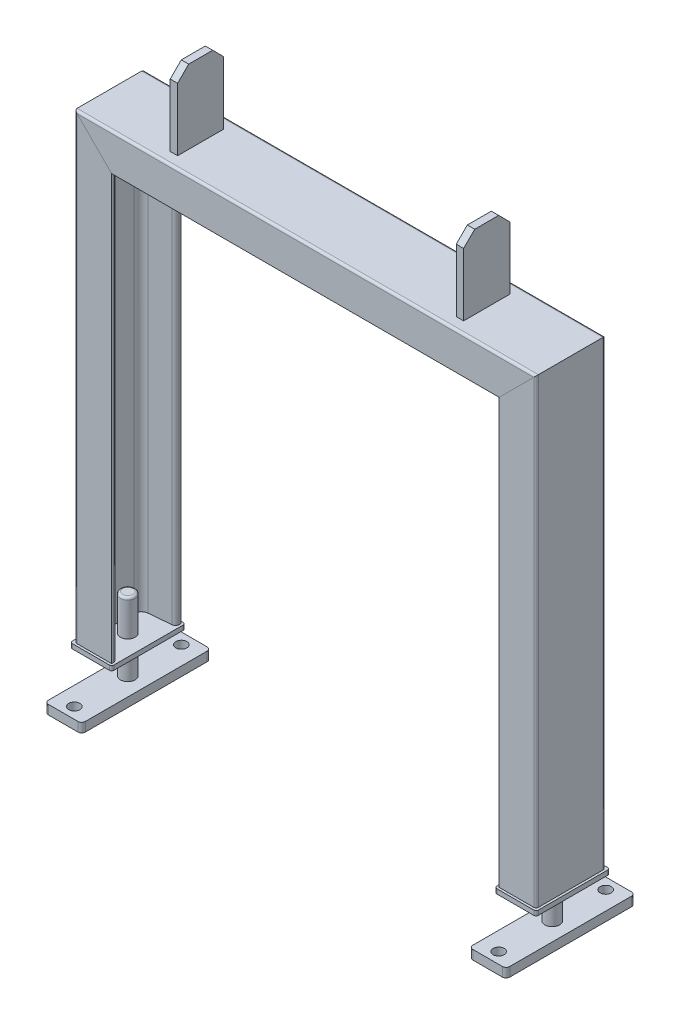
SolidWorks part; units mm, degrees
material "AISI 1015 Steel, Cold Drawn (SS)"
ref_plane "Front Plane" through (0, 0, 0) normal (0, 0, 1) x (1, 0, 0)
ref_plane "Top Plane" through (0, 0, 0) normal (0, 1, 0) x (1, 0, 0)
ref_plane "Right Plane" through (0, 0, 0) normal (1, 0, 0) x (0, 0, -1)
sketch "Sketch1" plane through (0, 0, 0) normal (0, 0, 1) x (1, 0, 0)
  line L0 (250, 0) -> (-250, 0)
  line L1 (-250, 0) -> (-250, -500)
  line L2 (250, 0) -> (250, -500)
  point P4 (0, 0)
  dimension "D1" = 500
  dimension "D2" = 500
other "Channel C 75 X 40 X 5.0(1)"
ref_plane "Plane1" through (-250, 0, -37.5) normal (0, -1, 0) x (1, 0, 0)
sketch "Sketch14" plane through (-250, 0, -37.5) normal (0, -1, 0) x (1, 0, 0)
  line L0 (40, 75) -> (0, 75)
  line L1 (40, 0) -> (0, 0)
  line L2 (0, 75) -> (0, 0)
  line L5 (0, 7) -> (22.5, 7) construction
  line L6 (40, 75) -> (40, 73.1964)
  line L7 (40, 0) -> (40, 1.8036)
  line L8 (5, 37.5) -> (0, 37.5) construction
  line L12 (5, 59.1383) -> (5, 15.8617)
  line L17 (12.3028, 67.1079) -> (36.3486, 69.2116)
  line L18 (12.3028, 7.8921) -> (36.3486, 5.7884)
  arc A0 (36.3486, 69.2116) -> (40, 73.1964) centre (36, 73.1964) ccw
  arc A1 (36.3486, 5.7884) -> (40, 1.8036) centre (36, 1.8036) cw
  arc A9 (5, 15.8617) -> (12.3028, 7.8921) centre (13, 15.8617) ccw
  arc A10 (5, 59.1383) -> (12.3028, 67.1079) centre (13, 59.1383) cw
  point P10 (20, 75)
  point P11 (20, 0)
  point P14 (0, 0)
  dimension "D4" = 17.5
  dimension "RI" = 8
  dimension "D2" = 5
  dimension "RA" = 4
  dimension "Depth" = 75
  dimension "BF" = 40
  dimension "TW" = 5
  dimension "TF" = 7
sketch "Sketch15" plane through (0, -500, 0) normal (0, -1, 0) x (1, 0, 0)
  line L0 (-252.5, 37.5) -> (-252.5, -37.5)
  line L1 (-250, 37.5) -> (-210, 37.5) construction
  line L3 (-250, -37.5) -> (-210, -37.5) construction
  line L5 (250, -37.5) -> (210, -37.5) construction
  line L6 (250, -37.5) -> (250, 37.5) construction
  line L7 (250, 37.5) -> (210, 37.5) construction
  line L8 (210, -37.5) -> (210, 37.5) construction
  line L9 (-250, -40) -> (-210, -40)
  line L10 (-207.5, 37.5) -> (-207.5, -37.5)
  line L11 (-250, 40) -> (-210, 40)
  line L12 (252.5, -37.5) -> (252.5, 37.5)
  line L13 (250, 40) -> (210, 40)
  line L14 (207.5, -37.5) -> (207.5, 37.5)
  line L15 (250, -40) -> (210, -40)
  line L16 (252.5, 40) -> (207.5, 40) construction
  line L17 (252.5, -40) -> (252.5, 40) construction
  line L18 (207.5, -40) -> (207.5, 40) construction
  line L19 (252.5, -40) -> (207.5, -40) construction
  line L20 (-252.5, 40) -> (-252.5, -40) construction
  line L21 (-252.5, -40) -> (-207.5, -40) construction
  line L22 (-207.5, 40) -> (-207.5, -40) construction
  line L23 (-252.5, 40) -> (-207.5, 40) construction
  line L24 (-250, 37.5) -> (-250, -37.5) construction
  line L25 (-210, 37.5) -> (-210, -37.5) construction
  line L26 (0, -55) -> (0, 55) construction
  line L27 (-210, 37.5) -> (-250, 37.5) construction
  line L28 (-210, 37.5) -> (-210, -37.5) construction
  line L29 (-210, -37.5) -> (-250, -37.5) construction
  line L30 (-250, 37.5) -> (-250, -37.5) construction
  line L31 (-210, 37.5) -> (-250, -37.5) construction
  line L32 (-210, -37.5) -> (-250, 37.5) construction
  arc A0 (250, 40) -> (252.5, 37.5) centre (250, 37.5) cw
  arc A1 (210, 40) -> (207.5, 37.5) centre (210, 37.5) ccw
  arc A2 (207.5, -37.5) -> (210, -40) centre (210, -37.5) ccw
  arc A3 (252.5, -37.5) -> (250, -40) centre (250, -37.5) cw
  arc A4 (-252.5, -37.5) -> (-250, -40) centre (-250, -37.5) ccw
  arc A5 (-210, -40) -> (-207.5, -37.5) centre (-210, -37.5) ccw
  arc A6 (-207.5, 37.5) -> (-210, 40) centre (-210, 37.5) ccw
  arc A7 (-250, 40) -> (-252.5, 37.5) centre (-250, 37.5) ccw
  circle A8 centre (-230, 0) radius 8
  circle A9 centre (230, 0) radius 8
  point P44 (-230, 0)
  dimension "D3" = 2.5
  dimension "D4" = 2.5
  dimension "D5" = 2.5
  dimension "D6" = 2.5
  dimension "D7" = 2.5
  dimension "D8" = 2.5
  dimension "D9" = 2.5
  dimension "D10" = 2.5
  dimension "D11" = 16
  dimension "D1" = 2.5
  dimension "D2" = 2.5
extrude "Boss-Extrude1" add sketch "Sketch15" along normal blind 5 separate body
fillet "Fillet1" radius 2.5 2 edges at (-250, -250, -37.5) (-250, -250, 37.5)
fillet "Fillet2" radius 2.5 2 edges at (0, 0, -37.5) (0, 0, 37.5)
fillet "Fillet3" radius 2.5 2 edges at (250, -250, -37.5) (250, -250, 37.5)
sketch "Sketch16" plane through (0, 0, 0) normal (0, 1, 0) x (1, 0, 0)
  line L0 (155, 0) -> (-155, 0)
  line L1 (0, -55) -> (0, 55) construction
  line L2 (-159, -25) -> (-151, -25)
  line L3 (-159, -25) -> (-159, 25)
  line L4 (-159, 25) -> (-151, 25)
  line L5 (-151, -25) -> (-151, 25)
  line L6 (-159, -25) -> (-151, 25) construction
  line L7 (-159, 25) -> (-151, -25) construction
  line L8 (159, 25) -> (151, -25) construction
  line L9 (159, -25) -> (151, 25) construction
  line L10 (151, -25) -> (151, 25)
  line L11 (159, 25) -> (151, 25)
  line L12 (159, -25) -> (159, 25)
  line L13 (159, -25) -> (151, -25)
  point P14 (0, 0)
  dimension "D1" = 8
  dimension "D2" = 50
  dimension "D3" = 151
extrude "Boss-Extrude2" add sketch "Sketch16" along normal blind 80 separate body
chamfer "Chamfer1" distance 12 2 edges at (-155, 80, -25) (-155, 80, 25)
chamfer "Chamfer2" distance 12 angle 45 2 edges at (155, 80, -25) (155, 80, 25)
sketch "Sketch17" plane through (0, -505, 0) normal (0, -1, 0) x (1, 0, 0)
  line L0 (0, -55) -> (0, 55) construction
  circle A0 centre (-230, 0) radius 8
  circle A1 centre (230, 0) radius 8
  dimension "D1" = 16
extrude "Boss-Extrude3" add sketch "Sketch17" along normal blind 35 and the other way blind 44 separate body
fillet "Fillet6" radius 2.5 1 edges at (-222, -461, 0)
fillet "Fillet7" radius 2.5 1 edges at (222, -461, 0)
sketch "Sketch18" plane through (0, -540, 0) normal (0, -1, 0) x (1, 0, 0)
  line L0 (-230, -58) -> (-230, 58) construction
  line L1 (-246, -70) -> (-214, -70)
  line L2 (-250, -66) -> (-250, 66)
  line L3 (-246, 70) -> (-214, 70)
  line L4 (-210, -66) -> (-210, 66)
  line L5 (-246, -66) -> (-214, 66) construction
  line L6 (-246, 66) -> (-214, -66) construction
  line L7 (0, -55) -> (0, 55) construction
  line L8 (246, 66) -> (214, -66) construction
  line L9 (246, -66) -> (214, 66) construction
  line L10 (230, -58) -> (230, 58) construction
  line L11 (210, -66) -> (210, 66)
  line L12 (246, 70) -> (214, 70)
  line L13 (250, -66) -> (250, 66)
  line L14 (246, -70) -> (214, -70)
  arc A0 (-250, -66) -> (-246, -70) centre (-246, -66) ccw
  arc A1 (-214, -70) -> (-210, -66) centre (-214, -66) ccw
  arc A2 (-214, 70) -> (-210, 66) centre (-214, 66) cw
  arc A3 (-246, 70) -> (-250, 66) centre (-246, 66) ccw
  circle A4 centre (-230, 58) radius 6
  circle A5 centre (-230, -58) radius 6
  circle A6 centre (230, -58) radius 6
  circle A7 centre (230, 58) radius 6
  arc A8 (246, 70) -> (250, 66) centre (246, 66) cw
  arc A9 (214, 70) -> (210, 66) centre (214, 66) ccw
  arc A10 (214, -70) -> (210, -66) centre (214, -66) cw
  arc A11 (250, -66) -> (246, -70) centre (246, -66) cw
  point P0 (-230, 0)
  point P25 (-230, 0)
  point P37 (230, 0)
  dimension "D2" = 4
  dimension "D3" = 4
  dimension "D1" = 4
  dimension "D4" = 4
  dimension "D8" = 12
  dimension "D5" = 140
  dimension "D6" = 40
  dimension "D7" = 116
extrude "Boss-Extrude4" add sketch "Sketch18" along normal blind 10 separate body
